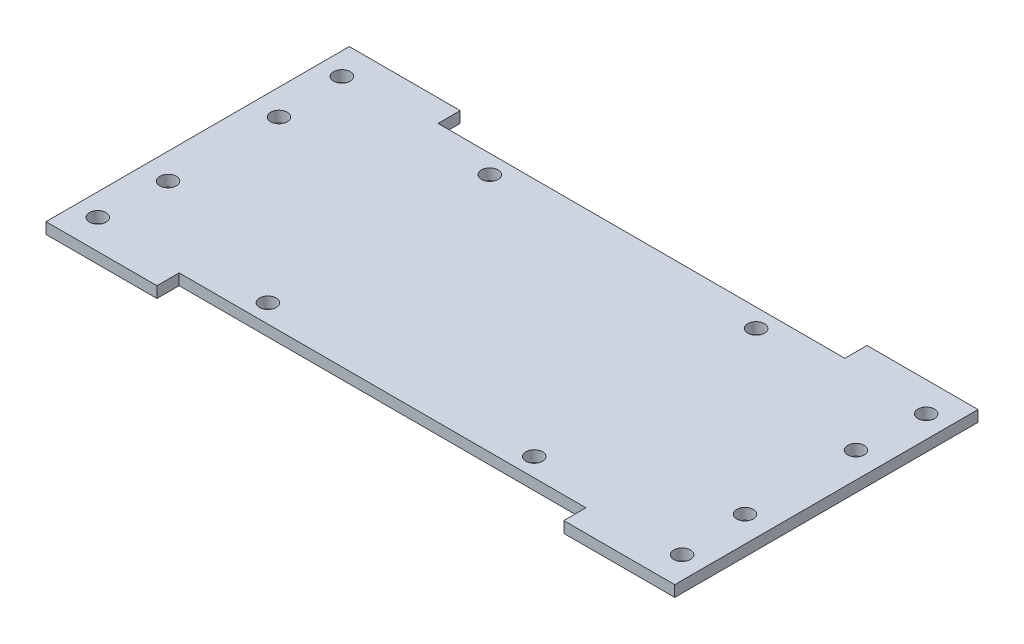
SolidWorks part; units mm, degrees
ref_plane "Front Plane" through (0, 0, 0) normal (0, 0, 1) x (1, 0, 0)
ref_plane "Top Plane" through (0, 0, 0) normal (0, 1, 0) x (1, 0, 0)
ref_plane "Right Plane" through (0, 0, 0) normal (1, 0, 0) x (0, 0, -1)
sketch "Sketch1" plane through (0, 0, 0) normal (0, 1, 0) x (1, 0, 0)
  line L1 (27.5, -17.5) -> (-27.5, -17.5)
  line L2 (27.5, -17.5) -> (27.5, 17.5)
  line L3 (27.5, 17.5) -> (-27.5, 17.5)
  line L4 (-27.5, -17.5) -> (-27.5, 17.5)
  line L5 (27.5, -17.5) -> (-27.5, 17.5) construction
  line L6 (27.5, 17.5) -> (-27.5, -17.5) construction
  point P0 (0, 0)
  dimension "D1" = 35
  dimension "D2" = 55
extrude "Boss-Extrude1" add sketch "Sketch1" along normal blind 1.5
sketch "Sketch2" plane through (0, 0, 0) normal (0, 1, 0) x (1, 0, 0)
  line L0 (-27.5, -17.5) -> (-27.5, 17.5) construction
  line L1 (42.5, -20.5) -> (27.5, -20.5)
  line L2 (42.5, -20.5) -> (42.5, 20.5)
  line L3 (42.5, 20.5) -> (27.5, 20.5)
  line L4 (27.5, -20.5) -> (27.5, 20.5)
  line L5 (-42.5, -20.5) -> (-27.5, -20.5)
  line L6 (-42.5, -20.5) -> (-42.5, 20.5)
  line L7 (-42.5, 20.5) -> (-27.5, 20.5)
  line L8 (-27.5, -20.5) -> (-27.5, 20.5)
  line L9 (27.5, -17.5) -> (27.5, 17.5) construction
  point P8 (-27.5, 0)
  point P11 (27.5, 0)
  point P12 (-42.5, 0)
  point P16 (42.5, 0)
  dimension "D1" = 15
  dimension "D2" = 15
  dimension "D3" = 41
  dimension "D4" = 41
extrude "Boss-Extrude2" add sketch "Sketch2" along normal up to surface (1.5 mm away) up to face at (0, 1.5, 0)
sketch "Sketch3" plane through (0, 0, 0) normal (0, 1, 0) x (1, 0, 0)
  line L0 (18, -15) -> (18, 15) construction
  line L1 (-18, -15) -> (-18, 15) construction
  line L2 (-18, -15) -> (18, -15) construction
  line L3 (-18, 15) -> (18, 15) construction
  line L4 (27.5, -17.5) -> (-27.5, -17.5) construction
  line L6 (27.5, 17.5) -> (-27.5, 17.5) construction
  line L7 (-39.5, -16.5) -> (-39.5, 16.5) construction
  line L8 (-39, -7.5) -> (-39, 7.5) construction
  line L9 (-42.5, -20.5) -> (-27.5, -20.5) construction
  line L10 (-27.5, 20.5) -> (-42.5, 20.5) construction
  line L11 (-42.5, 20.5) -> (-42.5, -20.5) construction
  circle A0 centre (-39.5, -16.5) radius 1.125
  circle A1 centre (-39, -7.5) radius 1.125
  circle A2 centre (-39, 7.5) radius 1.125
  circle A3 centre (-39.5, 16.5) radius 1.125
  circle A4 centre (-18, 15) radius 1.125
  circle A5 centre (18, 15) radius 1.125
  circle A6 centre (-18, -15) radius 1.125
  circle A7 centre (18, -15) radius 1.125
  point P20 (0, -15)
  dimension "D1" = 2.25
  dimension "D2" = 2.25
  dimension "D3" = 2.25
  dimension "D4" = 2.25
  dimension "D5" = 2.25
  dimension "D6" = 2.25
  dimension "D7" = 2.25
  dimension "D8" = 2.25
  dimension "D9" = 2.5
  dimension "D10" = 36
  dimension "3.5/2" = 2.5
  dimension "D11" = 4
  dimension "D12" = 4
  dimension "D13" = 3
  dimension "D14" = 3.5
  dimension "D15" = 13
  dimension "D16" = 13
extrude "Cut-Extrude1" cut sketch "Sketch3" along normal blind 10
mirror "Mirror1" about plane through (0, 0, 0) normal (1, 0, 0) of "Cut-Extrude1"
